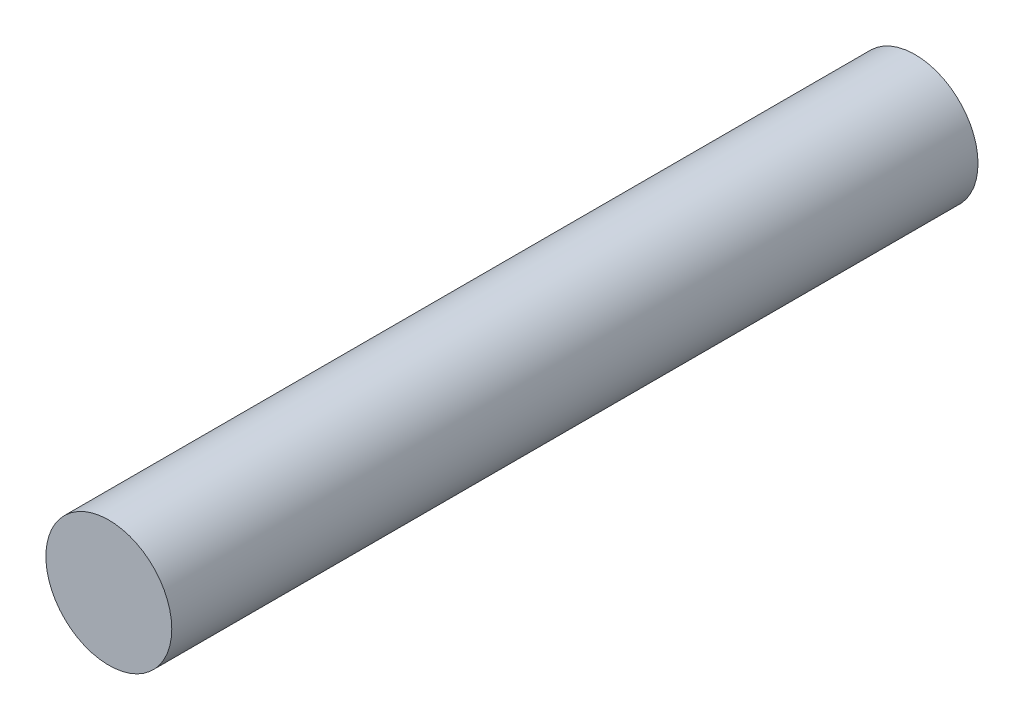
SolidWorks part; units mm, degrees
ref_plane "Front Plane" through (0, 0, 0) normal (0, 0, 1) x (1, 0, 0)
ref_plane "Top Plane" through (0, 0, 0) normal (0, 1, 0) x (1, 0, 0)
ref_plane "Right Plane" through (0, 0, 0) normal (1, 0, 0) x (0, 0, -1)
sketch "Sketch2" plane through (0, 0, 0) normal (0, 0, 1) x (1, 0, 0)
  circle A0 centre (0, 0) radius 1.1303
  dimension "D1" = 2.2606
extrude "Boss-Extrude1" add sketch "Sketch2" along normal blind 14.478
